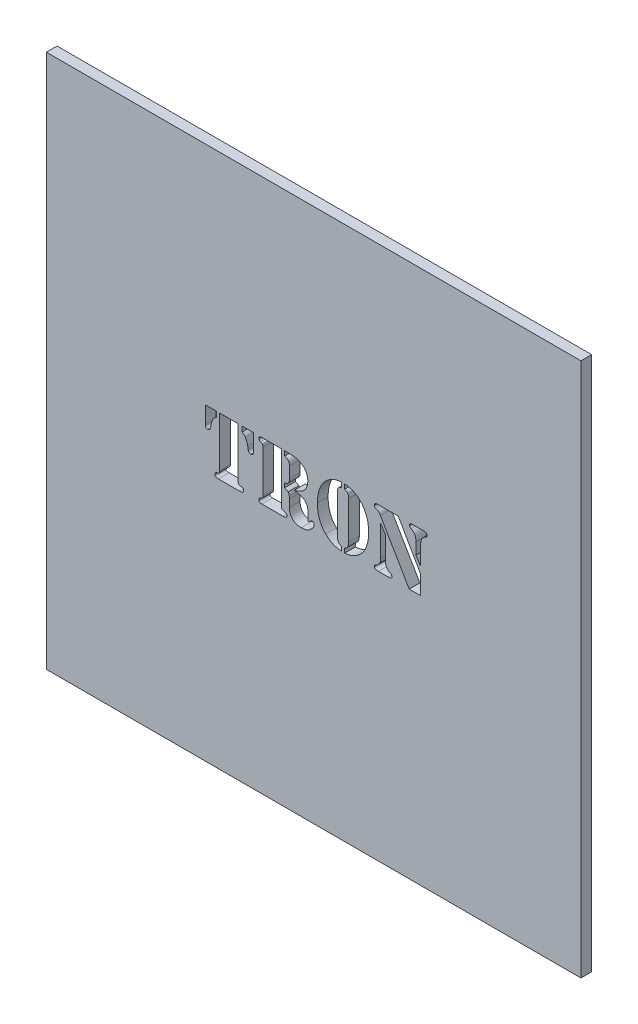
SolidWorks part; units mm, degrees
ref_plane "前视基准面" through (0, 0, 0) normal (0, 0, 1) x (1, 0, 0)
ref_plane "上视基准面" through (0, 0, 0) normal (0, 1, 0) x (1, 0, 0)
ref_plane "右视基准面" through (0, 0, 0) normal (1, 0, 0) x (0, 0, -1)
sketch "草图1" plane through (0, 0, 0) normal (0, 0, 1) x (1, 0, 0)
  line L1 (-45.5441, 29.6487) -> (54.4559, 29.6487)
  line L2 (-45.5441, 29.6487) -> (-45.5441, -70.3513)
  line L3 (-45.5441, -70.3513) -> (54.4559, -70.3513)
  line L4 (54.4559, 29.6487) -> (54.4559, -70.3513)
extrude "凸台-拉伸1" add sketch "草图1" along normal blind 2
sketch "草图2" plane through (0, 0, 2) normal (0, 0, 1) x (1, 0, 0)
  text T0 "TRON" font "Stencil" height in points 42
extrude "切除-拉伸1" cut sketch "草图2" against normal through all
